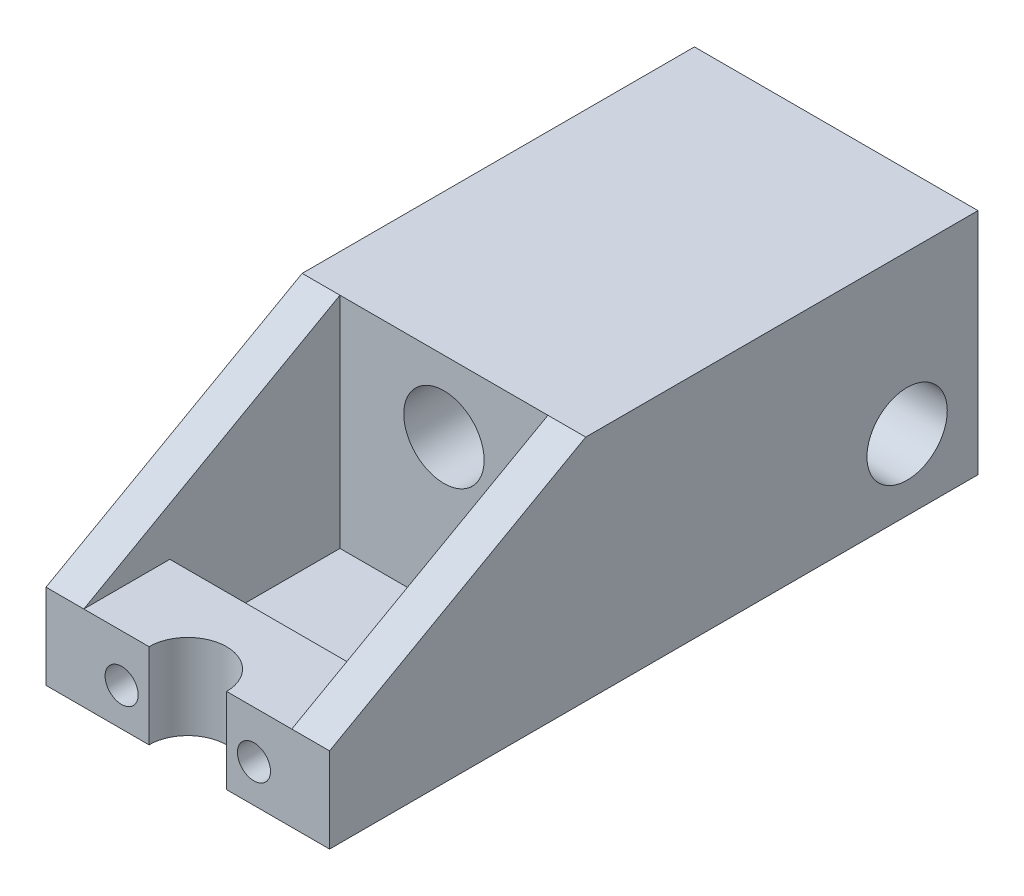
SolidWorks part; units mm, degrees
ref_plane "Piano frontale" through (0, 0, 0) normal (0, 0, 1) x (1, 0, 0)
ref_plane "Piano superiore" through (0, 0, 0) normal (0, 1, 0) x (1, 0, 0)
ref_plane "Piano destro" through (0, 0, 0) normal (1, 0, 0) x (0, 0, -1)
sketch "Schizzo7" plane through (0, 0, 0) normal (0, 0, 1) x (1, 0, 0)
  line L0 (0, -12.1) -> (0, 12.1) construction
  line L1 (15, -12.1) -> (-15, -12.1)
  line L2 (15, -12.1) -> (15, 12.1)
  line L3 (15, 12.1) -> (-15, 12.1)
  line L4 (-15, -12.1) -> (-15, 12.1)
  line L5 (15, -12.1) -> (-15, 12.1) construction
  line L6 (15, 12.1) -> (-15, -12.1) construction
  circle A0 centre (0, 4.6) radius 4.25
  point P0 (0, 0)
  point P10 (0, -4.6)
  dimension "D3" = 8.5
  dimension "D5" = 7.5
  dimension "D1" = 7.5
  dimension "D2" = 30
  dimension "D4" = 9.2
extrude "Estrusione-Estrusione3" add sketch "Schizzo7" along normal mid plane 15
sketch "Schizzo8" plane through (15, 0, 0) normal (1, 0, 0) x (0, 0, -1)
  line L0 (0, 12.1) -> (0, -12.1) construction
  line L1 (-7.5, 12.1) -> (7.5, 12.1) construction
  line L2 (-7.5, -12.1) -> (7.5, -12.1) construction
  circle A0 centre (0, -4.6) radius 4.25
  dimension "D2" = 8.5
  dimension "D1" = 7.5
extrude "Taglio-Estrusione1" cut sketch "Schizzo8" against normal up to next
sketch "Schizzo12" plane through (0, 0, 7.5) normal (0, 0, 1) x (1, 0, 0)
  line L0 (15, -12.1) -> (15, 12.1) construction
  line L1 (-15, -12.1) -> (15, -12.1)
  line L2 (-15, -12.1) -> (-15, -3.1)
  line L3 (-15, -3.1) -> (15, -3.1)
  line L4 (15, -12.1) -> (15, -3.1)
  dimension "D1" = 9
extrude "Estrusione-Estrusione5" add sketch "Schizzo12" along normal blind 53.6
sketch "Schizzo14" plane through (0, -3.1, 0) normal (0, 1, 0) x (1, 0, 0)
  line L0 (15, -61.1) -> (-15, -61.1) construction
  line L1 (4.1, -61.1) -> (-4.1, -61.1)
  arc A0 (4.1, -61.1) -> (-4.1, -61.1) centre (0, -61.1) ccw
  dimension "D1" = 4.1
extrude "Taglio-Estrusione3" cut sketch "Schizzo14" against normal up to next contours A0 L1
sketch "Schizzo15" plane through (0, -3.1, 0) normal (0, 1, 0) x (1, 0, 0)
  line L0 (15, -61.1) -> (4.1, -61.1) construction
  line L1 (0, -57) -> (0, -7.5) construction
  line L2 (15, -7.5) -> (-15, -7.5) construction
  line L3 (11, -52) -> (11, -34)
  line L4 (11, -34) -> (-11, -34)
  line L5 (-11, -52) -> (-11, -34)
  line L7 (15, -61.1) -> (15, -7.5) construction
  line L12 (11, -52) -> (-11, -52)
  arc A0 (4.1, -61.1) -> (-4.1, -61.1) centre (0, -61.1) ccw construction
  point P17 (0, -34)
  point P18 (0, -52)
  dimension "D1" = 9.1
  dimension "D2" = 18
  dimension "D4" = 4
sketch "Schizzo16" plane through (0, 0, 61.1) normal (0, 0, 1) x (1, 0, 0)
  line L0 (-4.1, -12.1) -> (4.1, -12.1) construction
  line L1 (-4.1, -12.1) -> (4.1, -12.1) construction
  line L2 (4.1, -3.1) -> (-4.1, -3.1) construction
  line L3 (4.1, -3.1) -> (-4.1, -3.1) construction
  line L4 (0, -12.1) -> (0, -3.1) construction
  line L5 (-4.1, -3.1) -> (-15, -3.1) construction
  circle A0 centre (-7, -8.1) radius 1.75
  circle A1 centre (7, -8.1) radius 1.75
  dimension "D2" = 3.5
  dimension "D1" = 5
  dimension "D3" = 7
extrude "Taglio-Estrusione4" cut sketch "Schizzo15" against normal blind 8
extrude "Taglio-Estrusione5" cut sketch "Schizzo16" against normal up to next
sketch "Schizzo17" plane through (0, 0, 52) normal (0, 0, -1) x (-1, 0, 0)
  line L0 (0, -3.1) -> (0, -11.1) construction
  line L1 (-3.75, -8.1) -> (-5.375, -5.2854)
  line L2 (-5.375, -5.2854) -> (-8.625, -5.2854)
  line L3 (-8.625, -5.2854) -> (-10.25, -8.1)
  line L4 (-10.25, -8.1) -> (-8.625, -10.9146)
  line L5 (-8.625, -10.9146) -> (-5.375, -10.9146)
  line L6 (-5.375, -10.9146) -> (-3.75, -8.1)
  line L7 (11, -3.1) -> (-11, -3.1) construction
  line L8 (11, -11.1) -> (-11, -11.1) construction
  line L9 (5.375, -10.9146) -> (3.75, -8.1)
  line L10 (8.625, -10.9146) -> (5.375, -10.9146)
  line L11 (10.25, -8.1) -> (8.625, -10.9146)
  line L12 (8.625, -5.2854) -> (10.25, -8.1)
  line L13 (5.375, -5.2854) -> (8.625, -5.2854)
  line L14 (3.75, -8.1) -> (5.375, -5.2854)
  circle A0 centre (-7, -8.1) radius 1.75 construction
  circle A1 centre (-7, -8.1) radius 1.75 construction
  circle A2 centre (-7, -8.1) radius 2.8146 construction
  circle A3 centre (7, -8.1) radius 2.8146 construction
  circle A4 centre (7, -8.1) radius 1.75 construction
  dimension "D1" = 6.5
extrude "Taglio-Estrusione6" cut sketch "Schizzo17" against normal blind 3.1 contours L1 L2 L3 L4 L5 L6 | L14 L13 L12 L11 L10 L9
sketch "Schizzo20" plane through (0, 0, 7.5) normal (0, 0, 1) x (1, 0, 0)
  line L4 (-15, -3.1) -> (15, -3.1)
  line L5 (15, -3.1) -> (15, 12.1)
  line L6 (15, 12.1) -> (-15, 12.1)
  line L7 (-15, 12.1) -> (-15, -3.1)
  line L8 (-15, -3.1) -> (15, -3.1)
  line L9 (15, -3.1) -> (15, 12.1)
  line L10 (15, 12.1) -> (-15, 12.1)
  line L11 (-15, 12.1) -> (-15, -3.1)
  line M5 (-15, -3.1) -> (15, -3.1)
  line M6 (15, -3.1) -> (15, 12.1)
  line M7 (15, 12.1) -> (-15, 12.1)
  line M8 (-15, 12.1) -> (-15, -3.1)
  circle M9 centre (0, 4.6) radius 4.25
  dimension "D1" = 0
extrude "Estrusione-Estrusione6" add sketch "Schizzo20" along normal up to vertex contours M8 M5 M6 M7 M9
sketch "Schizzo21" plane through (-15, 0, 0) normal (-1, 0, 0) x (0, 0, 1)
  line L0 (34, 12.1) -> (61.1, -3.1)
  line L1 (61.1, -3.1) -> (34, -3.1)
  line L2 (34, -3.1) -> (34, 12.1)
extrude "Estrusione-Estrusione7" add sketch "Schizzo21" against normal up to vertex (4 mm away) up to point (-11, -3.1, 52)
sketch "Schizzo22" plane through (15, 0, 0) normal (1, 0, 0) x (0, 0, -1)
  line L0 (-34, 12.1) -> (-61.1, -3.1)
  line L1 (-61.1, -3.1) -> (-34, -3.1)
  line L2 (-34, -3.1) -> (-34, 12.1)
extrude "Estrusione-Estrusione8" add sketch "Schizzo22" against normal up to vertex
